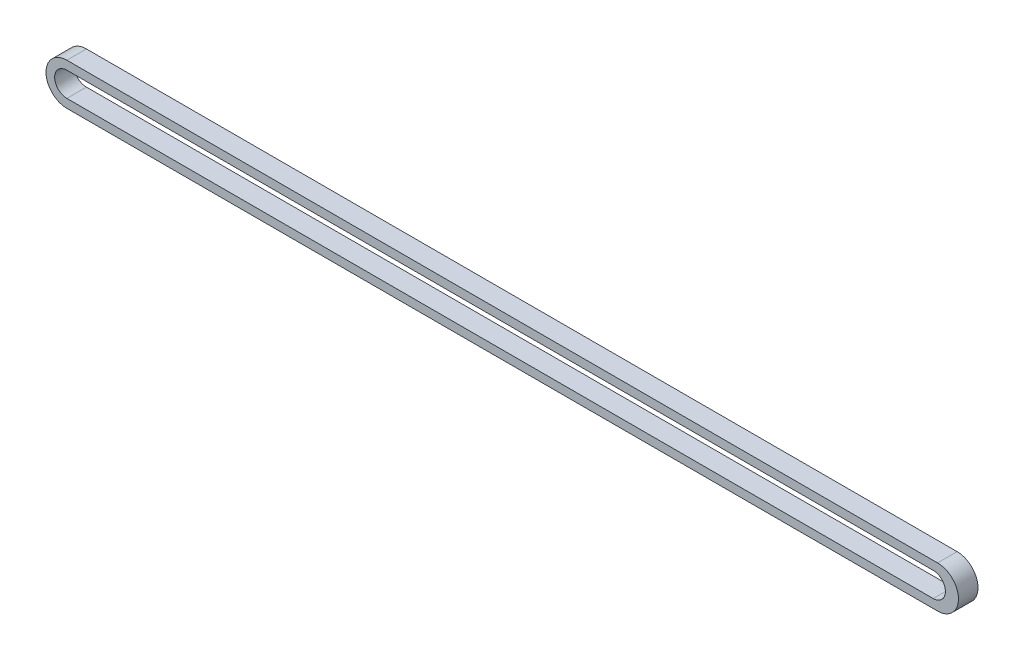
SolidWorks part; units mm, degrees
ref_plane "Front Plane" through (0, 0, 0) normal (0, 0, 1) x (1, 0, 0)
ref_plane "Top Plane" through (0, 0, 0) normal (0, 1, 0) x (1, 0, 0)
ref_plane "Right Plane" through (0, 0, 0) normal (1, 0, 0) x (0, 0, -1)
sketch "Sketch1" plane through (0, 0, 0) normal (0, 0, 1) x (1, 0, 0)
  line L0 (0, 0) -> (133.6, 0) construction
  line L1 (0, 3.2) -> (133.6, 3.2)
  line L2 (0, -3.2) -> (133.6, -3.2)
  line L3 (0, 0) -> (132.928, 0) construction
  line L4 (0, 1.872) -> (132.928, 1.872)
  line L5 (0, -1.872) -> (132.928, -1.872)
  arc A0 (0, 3.2) -> (0, -3.2) centre (0, 0) ccw
  arc A1 (133.6, -3.2) -> (133.6, 3.2) centre (133.6, 0) ccw
  circle A2 centre (133.6, 0) radius 0.672 construction
  arc A3 (0, 1.872) -> (0, -1.872) centre (0, 0) ccw
  arc A4 (132.928, -1.872) -> (132.928, 1.872) centre (132.928, 0) ccw
  circle A5 centre (0, 0) radius 3.2 construction
  circle A6 centre (0, 0) radius 1.872 construction
  point P4 (66.8, 0)
  point P9 (66.464, 0)
extrude "Boss-Extrude1" add sketch "Sketch1" against normal blind 3 contours L4 A4 L5 A3
